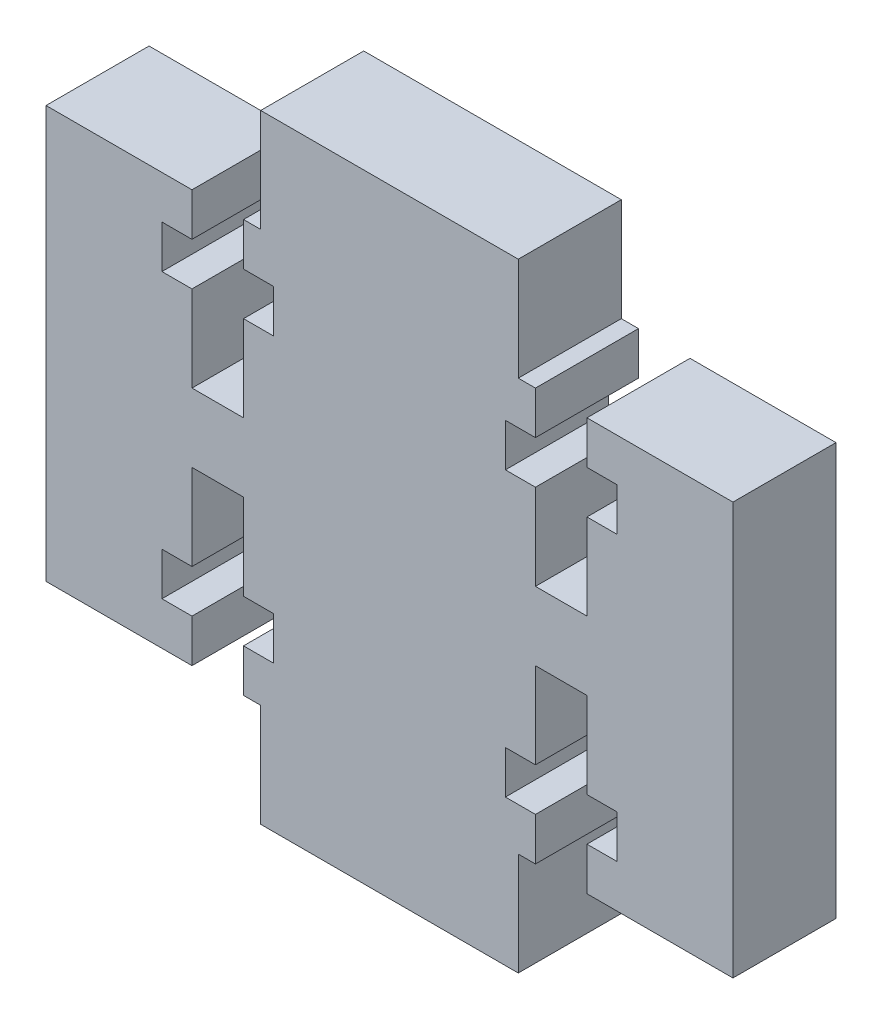
SolidWorks part; units mm, degrees
ref_plane "Front Plane" through (0, 0, 0) normal (0, 0, 1) x (1, 0, 0)
ref_plane "Top Plane" through (0, 0, 0) normal (0, 1, 0) x (1, 0, 0)
ref_plane "Right Plane" through (0, 0, 0) normal (1, 0, 0) x (0, 0, -1)
sketch "Sketch1" plane through (0, 0, 0) normal (0, 0, 1) x (1, 0, 0)
  line L0 (-1000, 0) -> (49000, 0) construction
  line L1 (0, -1000) -> (0, 49000) construction
  line L2 (-11.5, 12) -> (-8.5, 12)
  line L3 (-20, 12) -> (20, 12)
  line L4 (-20, 12) -> (-20, -12)
  line L5 (-20, -12) -> (20, -12)
  line L6 (20, 12) -> (20, -12)
  line L7 (-20, 12) -> (20, -12) construction
  line L8 (-20, -12) -> (20, 12) construction
  line L9 (-11.5, 12) -> (-11.5, 2)
  line L10 (-11.5, 2) -> (-8.5, 2)
  line L11 (-8.5, 12) -> (-8.5, 2)
  line L12 (-13.25, 9.5) -> (-6.75, 9.5)
  line L13 (-13.25, 9.5) -> (-13.25, 7)
  line L14 (-13.25, 7) -> (-6.75, 7)
  line L15 (-6.75, 9.5) -> (-6.75, 7)
  line L16 (-10, 12) -> (-10, -12) construction
  line L17 (10, 12) -> (10, -12) construction
  line L18 (6.75, 9.5) -> (6.75, 7)
  line L19 (13.25, 7) -> (6.75, 7)
  line L20 (13.25, 9.5) -> (13.25, 7)
  line L21 (13.25, 9.5) -> (6.75, 9.5)
  line L22 (8.5, 12) -> (8.5, 2)
  line L23 (11.5, 2) -> (8.5, 2)
  line L24 (11.5, 12) -> (11.5, 2)
  line L25 (11.5, 12) -> (8.5, 12)
  line L26 (11.5, -12) -> (8.5, -12)
  line L27 (11.5, -12) -> (11.5, -2)
  line L28 (11.5, -2) -> (8.5, -2)
  line L29 (8.5, -12) -> (8.5, -2)
  line L30 (13.25, -9.5) -> (6.75, -9.5)
  line L31 (13.25, -9.5) -> (13.25, -7)
  line L32 (13.25, -7) -> (6.75, -7)
  line L33 (6.75, -9.5) -> (6.75, -7)
  line L34 (-6.75, -9.5) -> (-6.75, -7)
  line L35 (-13.25, -7) -> (-6.75, -7)
  line L36 (-13.25, -9.5) -> (-13.25, -7)
  line L37 (-13.25, -9.5) -> (-6.75, -9.5)
  line L38 (-8.5, -12) -> (-8.5, -2)
  line L39 (-11.5, -2) -> (-8.5, -2)
  line L40 (-11.5, -12) -> (-11.5, -2)
  line L41 (-11.5, -12) -> (-8.5, -12)
  line L42 (7.5, -12) -> (-7.5, -18) construction
  line L43 (7.5, 18) -> (-7.5, 18)
  line L44 (7.5, 18) -> (7.5, 12)
  line L45 (7.5, 12) -> (-7.5, 12)
  line L46 (-7.5, 18) -> (-7.5, 12)
  line L47 (7.5, 18) -> (-7.5, 12) construction
  line L48 (7.5, 12) -> (-7.5, 18) construction
  line L49 (7.5, -18) -> (-7.5, -12) construction
  line L50 (-7.5, -18) -> (-7.5, -12)
  line L51 (7.5, -12) -> (-7.5, -12)
  line L52 (7.5, -18) -> (7.5, -12)
  line L53 (7.5, -18) -> (-7.5, -18)
  point P4 (0, 0)
  point P46 (0, 15)
  point P51 (0, 0)
  point P56 (0, -15)
  dimension "D1" = 10
  dimension "D2" = 3
  dimension "D3" = 6.5
  dimension "D4" = 2.5
  dimension "D5" = 5
  dimension "D6" = 10
  dimension "D7" = 10
  dimension "D8" = 40
  dimension "D9" = 24
  dimension "D10" = 6
  dimension "D11" = 15
extrude "Boss-Extrude1" add sketch "Sketch1" along normal blind 6 contours L5 L40 L37 L36 L35 L39 L38 L34 L29 L30 L33 L32 L28 L27 L31 L6 L3 L24 L21 L20 L19 L23 L22 L18 L11 L12 L15 L14 L10 L9 L13 | L43 L46 L3 L44 | L53 L52 L5 L50
equation "\"Frame_Size\" = 220"
equation "\"Frame_Thickness\" = 6"
equation "\"Arm_Width\" = 30"
equation "\"Motor_Mount_Hole_Diameter\" = 8"
equation "\"Motor_Shaft_Diameter\" = 3"
equation "\"Screw_Nut_Diameter\" = 6.5"
equation "\"Screw_Nut_Thickness\" = 2.5"
equation "\"Screw_Diameter\" = 3"
equation "\"Screw_Shaft_Length\" = 10"
equation "\"Screw_Hole_Separation_C2C\" = 20"
equation "\"Solder_Board_Small_Screw_Hole_Separation\" = 37"
equation "\"Solder_Board_Small_Screw_Hole_Diameter\" = 3.3"
equation "\"Solder_Board_Small_Length\" = 45.72"
equation "\"Solder_Board_Small_Width\" = 33.02"
equation "\"Solder_Board_Small_Thickness\" = 1.6"
equation "\"ESC_Length\" = 35"
equation "\"ESC_Width\" = 17"
equation "\"ESC_Thickness\" = 5"
equation "\"Battery_Length\" = 105"
equation "\"Battery_Width\" = 33"
equation "\"Battery_Thickness\" = 24"
equation "\"Battery_Holder_Screw_Hole_Distance_Long\" = 110"
equation "\"Battery_Holder_Screw_Hole_Distance_Short\" = 40"
equation "\"D5@Sketch1\"=\"Screw_Shaft_Length\"/2"
equation "\"D1@Sketch1\"=\"Screw_Shaft_Length\""
equation "\"D3@Sketch1\"=\"Screw_Nut_Diameter\""
equation "\"D2@Sketch1\"=\"Screw_Diameter\""
equation "\"D4@Sketch1\"=\"Screw_Nut_Thickness\""
equation "\"D6@Sketch1\"=\"Battery_Holder_Screw_Hole_Distance_Short\"/4"
equation "\"D7@Sketch1\"=\"Battery_Holder_Screw_Hole_Distance_Short\"/4"
equation "\"D8@Sketch1\"=\"Battery_Holder_Screw_Hole_Distance_Short\""
equation "\"D9@Sketch1\"=\"Battery_Thickness\""
equation "\"D1@Boss-Extrude1\"=\"Frame_Thickness\""
equation "\"D10@Sketch1\"=\"Frame_Thickness\""
equation "\"Tooth_Width\" = 15"
equation "\"D11@Sketch1\"=\"Tooth_Width\""
